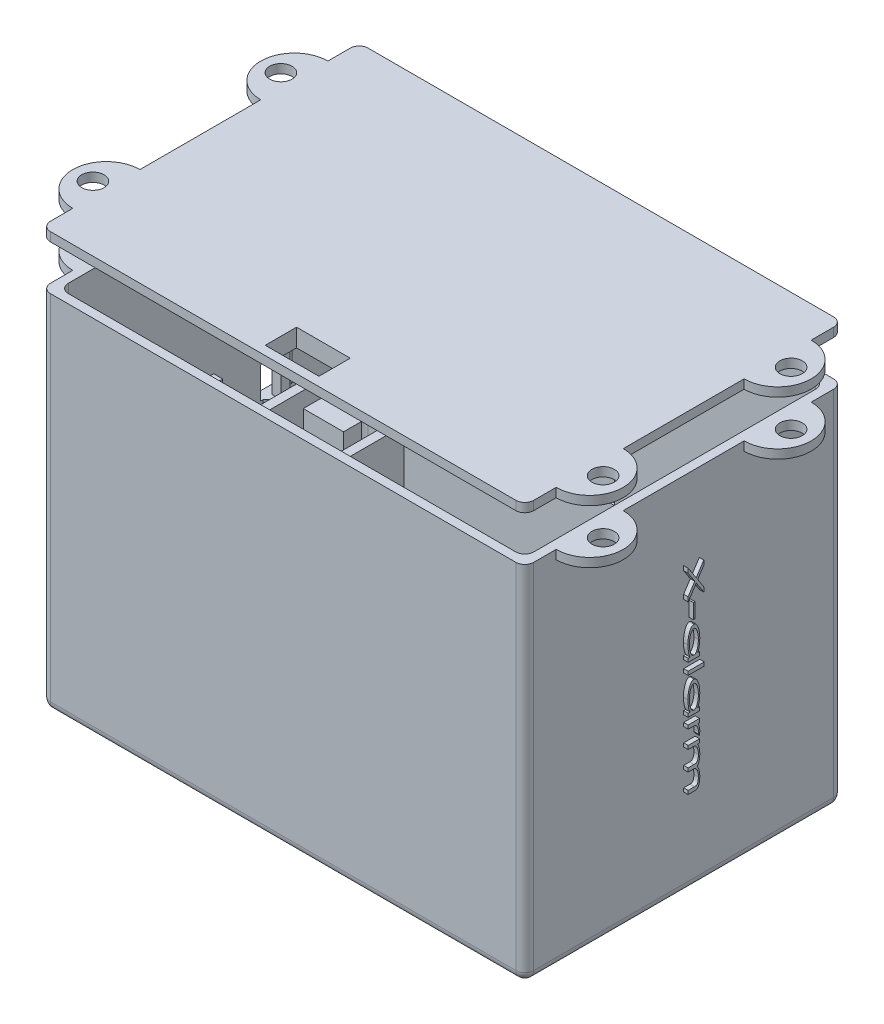
SolidWorks part; units mm, degrees
ref_plane "Top Plane" through (0, 0, 0) normal (0, 0, 1) x (1, 0, 0)
ref_plane "Front Plane" through (0, 0, 0) normal (0, 1, 0) x (1, 0, 0)
ref_plane "Right Plane" through (0, 0, 0) normal (1, 0, 0) x (0, 0, -1)
sketch "Sketch1" plane through (0, 0, 0) normal (0, 1, 0) x (1, 0, 0)
  line L9 (-54, -35.5) -> (54, -35.5)
  line L10 (-54, -35.5) -> (-54, 35.5)
  line L19 (-54, 35.5) -> (54, 35.5)
  line L20 (54, -35.5) -> (54, 35.5)
  line L21 (-52, 33.5) -> (52, 33.5)
  line L22 (-52, 33.5) -> (-52, -33.5)
  line L27 (-52, -33.5) -> (52, -33.5)
  line L28 (52, 33.5) -> (52, -33.5)
  line L29 (-52, 33.5) -> (52, -33.5) construction
  line L30 (-52, -33.5) -> (52, 33.5) construction
  point P0 (0, 0)
  point P1 (0, 0)
  point P6 (0, 0)
extrude "box" add sketch "Sketch1" along normal blind 81
sketch "Sketch3" plane through (0, 0, 0) normal (0, -1, 0) x (1, 0, 0)
  line L1 (-54, -35.5) -> (54, -35.5)
  line L2 (-54, -35.5) -> (-54, 35.5)
  line L3 (-54, 35.5) -> (54, 35.5)
  line L4 (54, -35.5) -> (54, 35.5)
extrude "front" add sketch "Sketch3" against normal blind 2
fillet "Fillet" radius 2 4 edges at (54, 40.5, -35.5) (-54, 40.5, 35.5) (-54, 40.5, -35.5) (54, 40.5, 35.5)
fillet "Fillet_in" radius 2 4 edges at (-52, 41.5, 33.5) (52, 41.5, 33.5) (-52, 41.5, -33.5) (52, 41.5, -33.5)
fillet "Fillet2" radius 2 8 edges at (-53.4142, 0, 34.9142) (-53.4142, 0, -34.9142) (53.4142, 0, -34.9142) (53.4142, 0, 34.9142) (54, 0, 0) (0, 0, -35.5) (-54, 0, 0) (0, 0, 35.5)
fillet "Fillet2_in" radius 2 8 edges at (51.4142, 2, -32.9142) (51.4142, 2, 32.9142) (-51.4142, 2, 32.9142) (-51.4142, 2, -32.9142) (52, 2, 0) (0, 2, 33.5) (-52, 2, 0) (0, 2, -33.5)
sketch "Sketch4" plane through (0, 0, 0) normal (0, -1, 0) x (1, 0, 0)
  line L1 (-48.5, 20) -> (48.5, 20)
  line L2 (-48.5, 20) -> (-48.5, -20)
  line L3 (-48.5, -20) -> (48.5, -20)
  line L4 (48.5, 20) -> (48.5, -20)
  line L5 (-48.5, 20) -> (48.5, -20) construction
  line L6 (-48.5, -20) -> (48.5, 20) construction
  point P0 (0, 0)
extrude "lcd" cut sketch "Sketch4" against normal blind 54 and the other way blind 37
sketch "Sketch5" plane through (0, 0, 0) normal (0, -1, 0) x (1, 0, 0)
  circle A0 centre (-46, 27.5) radius 2
extrude "lcd_hole" cut sketch "Sketch5" against normal blind 142 and the other way blind 41
mirror "Mirror_for_lcd_holes" about plane through (0, 0, 0) normal (1, 0, 0) of "lcd_hole"
mirror "Mirror_for_lcd_holes2" about plane through (0, 0, 0) normal (0, 0, 1) of "Mirror_for_lcd_holes", "lcd_hole"
sketch "Sketch6" plane through (0, 0, -33.5) normal (0, 0, 1) x (1, 0, 0)
  line L0 (-52, 81) -> (52, 2) construction
  line L1 (-5, 49) -> (5, 49)
  line L2 (-5, 49) -> (-5, 34)
  line L3 (-5, 34) -> (5, 34)
  line L4 (5, 49) -> (5, 34)
  line L5 (-52, 2) -> (52, 81) construction
  line L6 (-5, 49) -> (5, 34) construction
  line L7 (-5, 34) -> (5, 49) construction
  point P10 (0, 41.5)
  point P11 (0, 41.5)
extrude "senceor" cut sketch "Sketch6" against normal blind 0.5
ref_plane "Plane_for_back" through (0, 91, 0) normal (0, 1, 0) x (1, 0, 0)
sketch "Sketch9" plane through (0, 91, 0) normal (0, 1, 0) x (1, 0, 0)
  line L1 (54, -35.5) -> (-54, -35.5)
  line L2 (54, -35.5) -> (54, 35.5)
  line L3 (54, 35.5) -> (-54, 35.5)
  line L4 (-54, -35.5) -> (-54, 35.5)
  line L5 (54, -35.5) -> (-54, 35.5) construction
  line L6 (54, 35.5) -> (-54, -35.5) construction
  line L7 (-4.0052, 35.5) -> (4.0052, 35.5)
  line L8 (-4.0052, 35.5) -> (4.0052, 35.5)
  point P0 (0, 0)
extrude "back" add sketch "Sketch9" along normal blind 2 separate body
fillet "Fillet_back" radius 2 4 edges at (54, 92, -35.5) (54, 92, 35.5) (-54, 92, 35.5) (-54, 92, -35.5)
sketch "Sketch10" plane through (0, 93, 0) normal (0, 1, 0) x (1, 0, 0)
  line L0 (-54, -33.5) -> (-54, 33.5) construction
  line L1 (-54, 28.5) -> (-54, 13.5)
  arc A0 (-54, 28.5) -> (-54, 13.5) centre (-54, 21) ccw
extrude "for_holes" add sketch "Sketch10" against normal blind 2
sketch "Sketch11" plane through (0, 93, 0) normal (0, 1, 0) x (1, 0, 0)
  circle A1 centre (-57, 21) radius 2.5
extrude "holes" cut sketch "Sketch11" against normal blind 2
mirror "Mirror_for_holes1_1" about plane through (0, 0, 0) normal (1, 0, 0) of "for_holes", "holes"
mirror "Mirror_for_holes1_2" about plane through (0, 0, 0) normal (0, 0, 1) of "Mirror_for_holes1_1", "for_holes", "holes"
sketch "Sketch12" plane through (0, 81, 0) normal (0, 1, 0) x (1, 0, 0)
  line L0 (-54, 28.5) -> (-54, 13.5)
  arc A0 (-54, 13.5) -> (-54, 28.5) centre (-54, 21) cw
  arc A1 (-54, 28.5) -> (-54, 13.5) centre (-54, 21) ccw construction
extrude "for_holes2" add sketch "Sketch12" against normal blind 2
sketch "Sketch13" plane through (0, 81, 0) normal (0, 1, 0) x (1, 0, 0)
  circle A0 centre (-57, 21) radius 2.5
extrude "holes2" cut sketch "Sketch13" against normal blind 2
mirror "Mirror_for_holes2_1" about plane through (0, 0, 0) normal (1, 0, 0) of "holes2", "for_holes2"
mirror "Mirror_for_holes2_2" about plane through (0, 0, 0) normal (0, 0, 1) of "Mirror_for_holes2_1", "for_holes2", "holes2"
sketch "Sketch15" plane through (-54, 0, 0) normal (-1, 0, 0) x (0, 0, 1)
  line L1 (-3.5, 36.729) -> (3.5, 36.729)
  line L2 (-3.5, 36.729) -> (-3.5, 43.729)
  line L3 (-3.5, 43.729) -> (3.5, 43.729)
  line L4 (3.5, 36.729) -> (3.5, 43.729)
  line L5 (-3.5, 36.729) -> (3.5, 43.729) construction
  line L6 (-3.5, 43.729) -> (3.5, 36.729) construction
  line L7 (-18.5, 36.729) -> (-11.5, 36.729)
  line L8 (-18.5, 36.729) -> (-18.5, 43.729)
  line L9 (-18.5, 43.729) -> (-11.5, 43.729)
  line L10 (-11.5, 36.729) -> (-11.5, 43.729)
  line L11 (-18.5, 36.729) -> (-11.5, 43.729) construction
  line L12 (-18.5, 43.729) -> (-11.5, 36.729) construction
  circle A2 centre (15, 40.229) radius 4
  point P0 (0, 40.229)
  point P8 (-15, 40.229)
  dimension "D1" = 15
  dimension "D2" = 15
  dimension "D3" = 8
  dimension "D4" = 7
  dimension "D5" = 7
  dimension "D6" = 7
  dimension "D7" = 7
extrude "datchiki" cut sketch "Sketch15" against normal blind 2
sketch "Sketch17" plane through (-52, 0, 0) normal (1, 0, 0) x (0, 0, -1)
  line L1 (1, 47.229) -> (-1, 47.229)
  line L2 (1, 47.229) -> (1, 33.229)
  line L3 (1, 33.229) -> (-1, 33.229)
  line L4 (-1, 47.229) -> (-1, 33.229)
  line L5 (1, 47.229) -> (-1, 33.229) construction
  line L6 (1, 33.229) -> (-1, 47.229) construction
  line L7 (-8.5, 33.729) -> (-21.5, 33.729)
  line L8 (-8.5, 33.729) -> (-8.5, 46.729)
  line L9 (-8.5, 46.729) -> (-21.5, 46.729)
  line L10 (-21.5, 33.729) -> (-21.5, 46.729)
  line L11 (-8.5, 33.729) -> (-21.5, 46.729) construction
  line L12 (-8.5, 46.729) -> (-21.5, 33.729) construction
  line L13 (-6.5, 31.729) -> (-23.5, 31.729)
  line L14 (-6.5, 31.729) -> (-6.5, 48.729)
  line L15 (-6.5, 48.729) -> (-23.5, 48.729)
  line L16 (-23.5, 31.729) -> (-23.5, 48.729)
  line L17 (-6.5, 31.729) -> (-23.5, 48.729) construction
  line L18 (-6.5, 48.729) -> (-23.5, 31.729) construction
  line L19 (16, 33.229) -> (14, 33.229)
  line L20 (16, 33.229) -> (16, 47.229)
  line L21 (16, 47.229) -> (14, 47.229)
  line L22 (14, 33.229) -> (14, 47.229)
  line L23 (16, 33.229) -> (14, 47.229) construction
  line L24 (16, 47.229) -> (14, 33.229) construction
  point P0 (0, 40.229)
  point P5 (-15, 40.229)
  point P11 (-15, 40.229)
  point P16 (15, 40.229)
  dimension "D1" = 15
  dimension "D2" = 15
  dimension "D3" = 2
  dimension "D4" = 2
  dimension "D5" = 14
  dimension "D6" = 14
  dimension "D7" = 13
  dimension "D8" = 17
  dimension "D9" = 17
  dimension "D10" = 13
extrude "knopki" add sketch "Sketch17" along normal blind 2 separate body
sketch "Sketch18" plane through (54, 0, 0) normal (1, 0, 0) x (0, 0, -1)
  line L0 (0, 81) -> (0, 2) construction
  line L1 (-13.5, 81) -> (13.5, 81) construction
  line L2 (-33.5, 2) -> (33.5, 2) construction
  text T0 "X-alarm" font "Century Gothic" height 3.5
extrude "Alarm" add sketch "Sketch18" along normal blind 1
sketch "Sketch19" plane through (0, 91, 0) normal (0, -1, 0) x (1, 0, 0)
  line L9 (-52, -33.5) -> (52, -33.5)
  line L10 (-52, -33.5) -> (-52, 33.5)
  line L11 (-52, 33.5) -> (52, 33.5)
  line L12 (52, -33.5) -> (52, 33.5)
extrude "back_fixed" add sketch "Sketch19" along normal blind 2
fillet "back_fixed_fillet" radius 2 4 edges at (-52, 90, 33.5) (52, 90, 33.5) (52, 90, -33.5) (-52, 90, -33.5)
sketch "Sketch20" plane through (0, 33.229, 0) normal (0, -1, 0) x (1, 0, 0)
  line L0 (-50, 1) -> (-52, 1)
  line L1 (-52, 1) -> (-52, 3)
  line L2 (-52, 3) -> (-50, 1)
  line L3 (-50, -14) -> (-52, -14)
  line L4 (-50, -14) -> (-52, -14) construction
  line L5 (-52, -14) -> (-52, -16) construction
  line L6 (-52, -14) -> (-52, -12)
  line L7 (-52, -12) -> (-50, -14)
extrude "podd" add sketch "Sketch20" against normal blind 3.5
sketch "Sketch24" plane through (0, 47.229, 0) normal (0, 1, 0) x (1, 0, 0)
  line L0 (-52, 14) -> (-50, 14)
  line L1 (-50, 14) -> (-52, 12)
  line L2 (-52, 12) -> (-52, 14)
  line L3 (-52, -1) -> (-50, -1)
  line L4 (-50, -1) -> (-52, -3)
  line L5 (-52, -3) -> (-52, -1)
extrude "podd2" add sketch "Sketch24" against normal blind 3.5
sketch "Sketch25" plane through (0, 48.729, 0) normal (0, 1, 0) x (1, 0, 0)
  line L0 (-52, -23.5) -> (-50, -23.5)
  line L1 (-50, -23.5) -> (-52, -25.5)
  line L2 (-52, -25.5) -> (-52, -23.5)
extrude "podd3" add sketch "Sketch25" against normal blind 17
sketch "Sketch22" plane through (0, 0, 33.5) normal (0, 0, -1) x (-1, 0, 0)
  line L1 (10, 31) -> (-10, 31)
  line L2 (10, 31) -> (10, 78)
  line L4 (-10, 31) -> (-10, 78)
  line L5 (10, 31) -> (-10, 78) construction
  line L6 (10, 78) -> (-10, 31) construction
  line L7 (10, 78) -> (8, 78)
  line L8 (8, 78) -> (8, 33)
  line L9 (8, 33) -> (-8, 33)
  line L10 (-8, 33) -> (-8, 78)
  line L11 (-8, 78) -> (-10, 78)
  point P0 (0, 54.5)
  dimension "D1" = 47
  dimension "D2" = 45
  dimension "D3" = 47
  dimension "D4" = 45
  dimension "D5" = 2
  dimension "D6" = 2
extrude "ardxuino" add sketch "Sketch22" along normal blind 15
sketch "Sketch23" plane through (0, 33, 0) normal (0, 1, 0) x (1, 0, 0)
  line L0 (-50, -33.5) -> (50, -33.5) construction
  line L1 (-4.5, -22.5) -> (4.5, -22.5)
  line L2 (-4.5, -22.5) -> (-4.5, -26.5)
  line L3 (-4.5, -26.5) -> (4.5, -26.5)
  line L4 (4.5, -22.5) -> (4.5, -26.5)
  line L5 (-8, -18.5) -> (-8, -33.5) construction
  line L6 (8, -18.5) -> (8, -33.5) construction
  dimension "D1" = 7
  dimension "D2" = 9
  dimension "D3" = 4
  dimension "D4" = 3.5
  dimension "D5" = 3.5
extrude "arduino2" add sketch "Sketch23" along normal blind 45
sketch "Sketch27" plane through (0, 89, 0) normal (0, -1, 0) x (1, 0, 0)
  line L0 (-10, 18.5) -> (-10, 33.5) construction
  line L1 (-6, 33.5) -> (6, 33.5)
  line L2 (-6, 33.5) -> (-6, 26.5)
  line L3 (-6, 26.5) -> (6, 26.5)
  line L4 (6, 33.5) -> (6, 26.5)
  line L5 (10, 18.5) -> (10, 33.5) construction
  line L6 (10, 33.5) -> (-10, 33.5) construction
  dimension "D1" = 12
  dimension "D2" = 7
  dimension "D3" = 4
  dimension "D4" = 4
  dimension "D5" = 0
extrude "port" cut sketch "Sketch27" against normal blind 4
sketch "Sketch28" plane through (10, 0, 0) normal (1, 0, 0) x (0, 0, -1)
  line L0 (-18.5, 31) -> (-33.5, 31)
  line L1 (-33.5, 31) -> (-33.5, 21)
  line L2 (-33.5, 21) -> (-18.5, 31)
extrude "podd_arduino" add sketch "Sketch28" against normal blind 20
